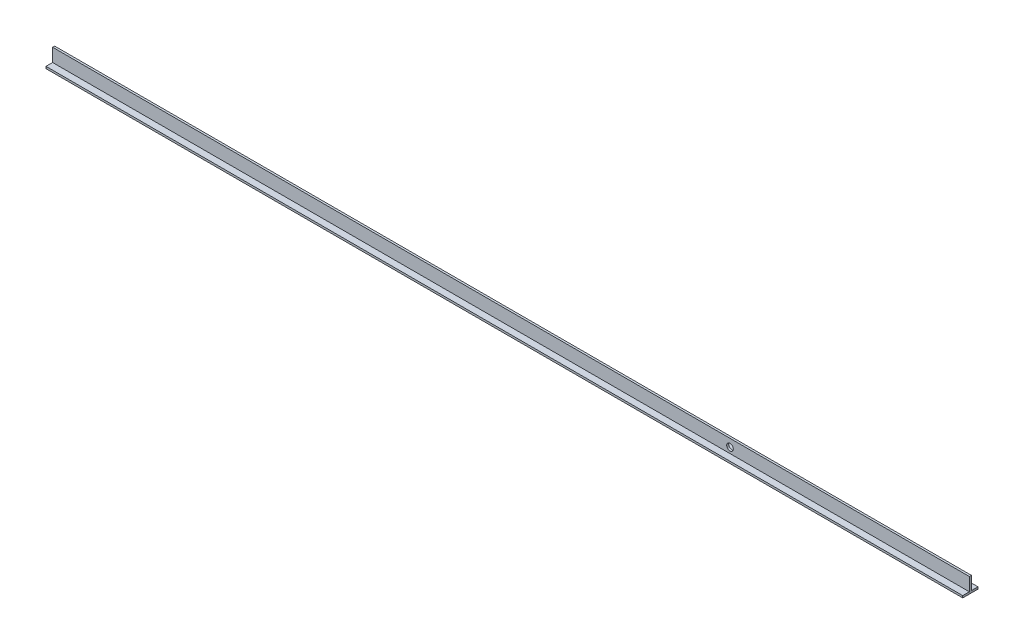
SolidWorks part; units mm, degrees
material "1.0037 (S235JR)"
ref_plane "Plan de face" through (0, 0, 0) normal (0, 0, 1) x (1, 0, 0)
ref_plane "Plan de dessus" through (0, 0, 0) normal (0, 1, 0) x (1, 0, 0)
ref_plane "Plan de droite" through (0, 0, 0) normal (1, 0, 0) x (0, 0, -1)
sketch "Esquisse1" plane through (0, 0, 0) normal (0, 0, 1) x (1, 0, 0)
  line L0 (900, 0) -> (-900, 0)
  point P4 (0, 0)
  dimension "D1" = 1800
other "Custom TE_30X30X4(1)"
ref_plane "Plan1" through (900, 0, 0) normal (-1, 0, 0) x (0, 0, 1)
sketch "Esquisse11" plane through (900, 0, 0) normal (-1, 0, 0) x (0, 0, 1)
  line L0 (-15, 0) -> (15, 0)
  line L5 (-15, 0) -> (-15, 4)
  line L6 (-15, 4) -> (-2, 4)
  line L11 (-2, 4) -> (-2, 30)
  line L12 (-2, 30) -> (2, 30)
  line L13 (2, 30) -> (2, 4)
  line L14 (2, 4) -> (15, 4)
  line L15 (15, 4) -> (15, 0)
  point P0 (0, 30)
  point P3 (0, 0)
  point P5 (0, 0)
  point P11 (-8.5, 4)
  point P12 (8.5, 4)
  point P13 (-15, 2)
  point P14 (15, 2)
  point P15 (0, 0)
  point P16 (2, 17)
  point P17 (-2, 17)
  point P18 (0, 4)
  point P19 (0, 17)
  dimension "D1" = 30
  dimension "D2" = 30
  dimension "D3" = 4
  dimension "D4" = 4
extrude "Enlèv. mat.-Extru.4" cut sketch "Esquisse15" against normal through all both and the other way through all
sketch "Esquisse15" plane through (430, 0, 50) normal (0, 0, 1) x (1, 0, 0)
  circle A3 centre (0, 15) radius 6.5
  circle A5 centre (0, 75) radius 6.5
